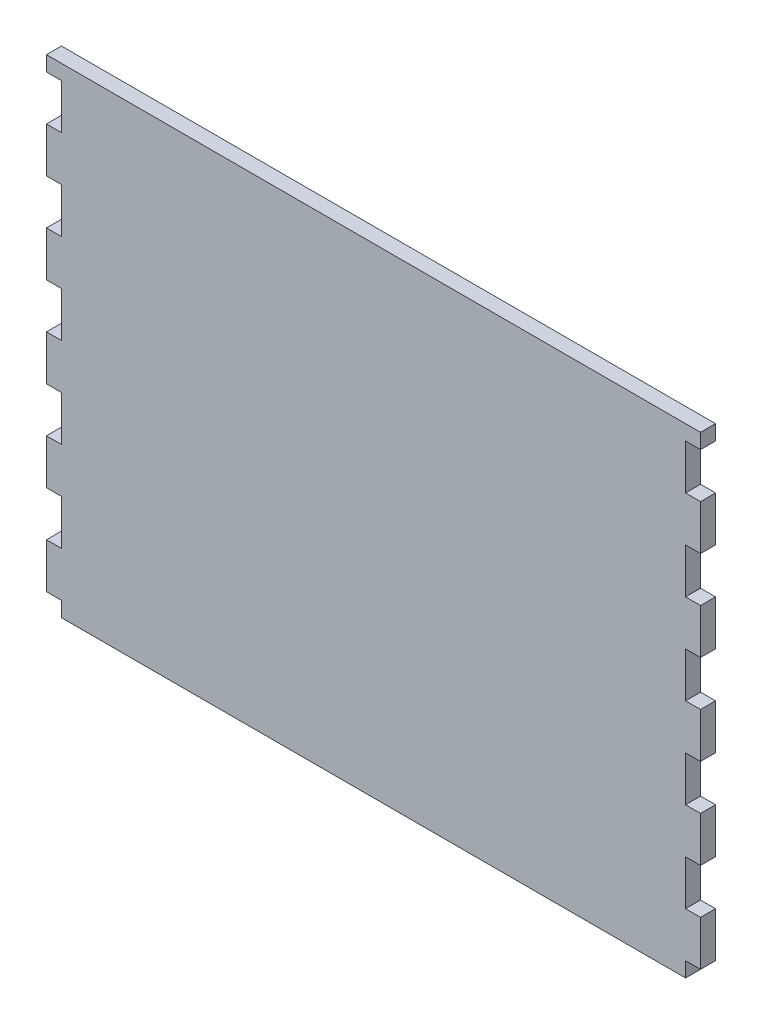
SolidWorks part; units mm, degrees
ref_plane "Front Plane" through (0, 0, 0) normal (0, 0, 1) x (1, 0, 0)
ref_plane "Top Plane" through (0, 0, 0) normal (0, 1, 0) x (1, 0, 0)
ref_plane "Right Plane" through (0, 0, 0) normal (1, 0, 0) x (0, 0, -1)
sketch "Sketch1" plane through (0, 0, 0) normal (0, 0, 1) x (1, 0, 0)
  line L1 (138.43, -101.6) -> (-138.43, -101.6)
  line L2 (138.43, -101.6) -> (138.43, 101.6)
  line L3 (138.43, 101.6) -> (-138.43, 101.6)
  line L4 (-138.43, -101.6) -> (-138.43, 101.6)
  line L5 (138.43, -101.6) -> (-138.43, 101.6) construction
  line L6 (138.43, 101.6) -> (-138.43, -101.6) construction
  point P0 (0, 0)
  dimension "D1" = 276.86
  dimension "D2" = 203.2
extrude "Boss-Extrude1" add sketch "Sketch1" along normal blind 6.35
sketch "Sketch2" plane through (0, 0, 6.35) normal (0, 0, 1) x (1, 0, 0)
  line L0 (-138.43, 101.6) -> (-138.43, -101.6) construction
  line L1 (-138.43, 95.25) -> (-132.08, 95.25)
  line L2 (-138.43, 95.25) -> (-138.43, 76.2)
  line L3 (-138.43, 76.2) -> (-132.08, 76.2)
  line L4 (-132.08, 95.25) -> (-132.08, 76.2)
  line L5 (138.43, 101.6) -> (-138.43, 101.6) construction
  dimension "D1" = 6.35
  dimension "D2" = 19.05
  dimension "D3" = 6.35
extrude "Cut-Extrude1" cut sketch "Sketch2" against normal through all
pattern_linear "LPattern1" count 6 spacing 38.1 along (0, -1, 0) of "Cut-Extrude1"
mirror "Mirror1" about plane through (0, 0, 0) normal (1, 0, 0) of "LPattern1", "Cut-Extrude1"
